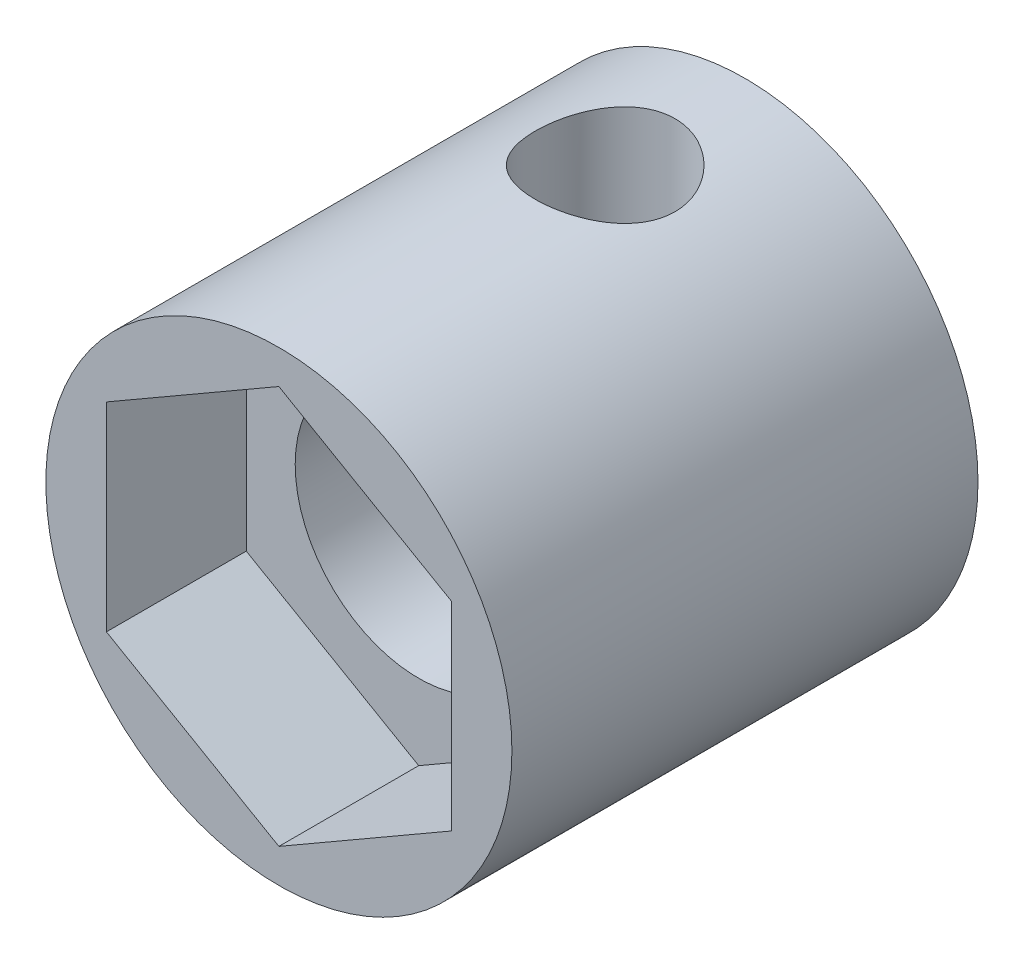
SolidWorks part; units mm, degrees
ref_plane "Plan de face" through (0, 0, 0) normal (0, 0, 1) x (1, 0, 0)
ref_plane "Plan de dessus" through (0, 0, 0) normal (0, 1, 0) x (1, 0, 0)
ref_plane "Plan de droite" through (0, 0, 0) normal (1, 0, 0) x (0, 0, -1)
sketch "Esquisse1" plane through (0, 0, 0) normal (0, 0, 1) x (1, 0, 0)
  circle A0 centre (0, 0) radius 5
  dimension "D1" = 10
extrude "Boss.-Extru.1" add sketch "Esquisse1" along normal blind 10
sketch "Esquisse2" plane through (0, 0, 10) normal (0, 0, 1) x (1, 0, 0)
  line L1 (3.7, -2.1362) -> (3.7, 2.1362)
  line L2 (3.7, 2.1362) -> (0, 4.2724)
  line L3 (0, 4.2724) -> (-3.7, 2.1362)
  line L4 (-3.7, 2.1362) -> (-3.7, -2.1362)
  line L5 (-3.7, -2.1362) -> (0, -4.2724)
  line L6 (0, -4.2724) -> (3.7, -2.1362)
  circle A0 centre (0, 0) radius 3.7 construction
  dimension "D1" = 7.4
extrude "Enlèv. mat.-Extru.1" cut sketch "Esquisse2" against normal blind 3
sketch "Esquisse3" plane through (0, 0, 0) normal (0, 0, -1) x (-1, 0, 0)
  circle A0 centre (0, 0) radius 2.65
  dimension "D1" = 5.3
extrude "Enlèv. mat.-Extru.2" cut sketch "Esquisse3" against normal blind 6
sketch "Esquisse4" plane through (0, 0, 0) normal (0, 1, 0) x (1, 0, 0)
  line L0 (0, 0) -> (0, -3) construction
  line L1 (5, 0) -> (-5, 0) construction
  line L2 (2.65, 0) -> (-2.65, 0) construction
  circle A0 centre (0, -3) radius 1.5
  dimension "D2" = 3
  dimension "D1" = 3
extrude "Enlèv. mat.-Extru.3" cut sketch "Esquisse4" against normal through all and the other way through all
sketch "Esquisse5" plane through (0, 0, 6) normal (0, 0, -1) x (-1, 0, 0)
  circle A0 centre (0, 0) radius 2.65
  circle A1 centre (0, 0) radius 2.65 construction
extrude "Enlèv. mat.-Extru.4" cut sketch "Esquisse5" against normal through all
